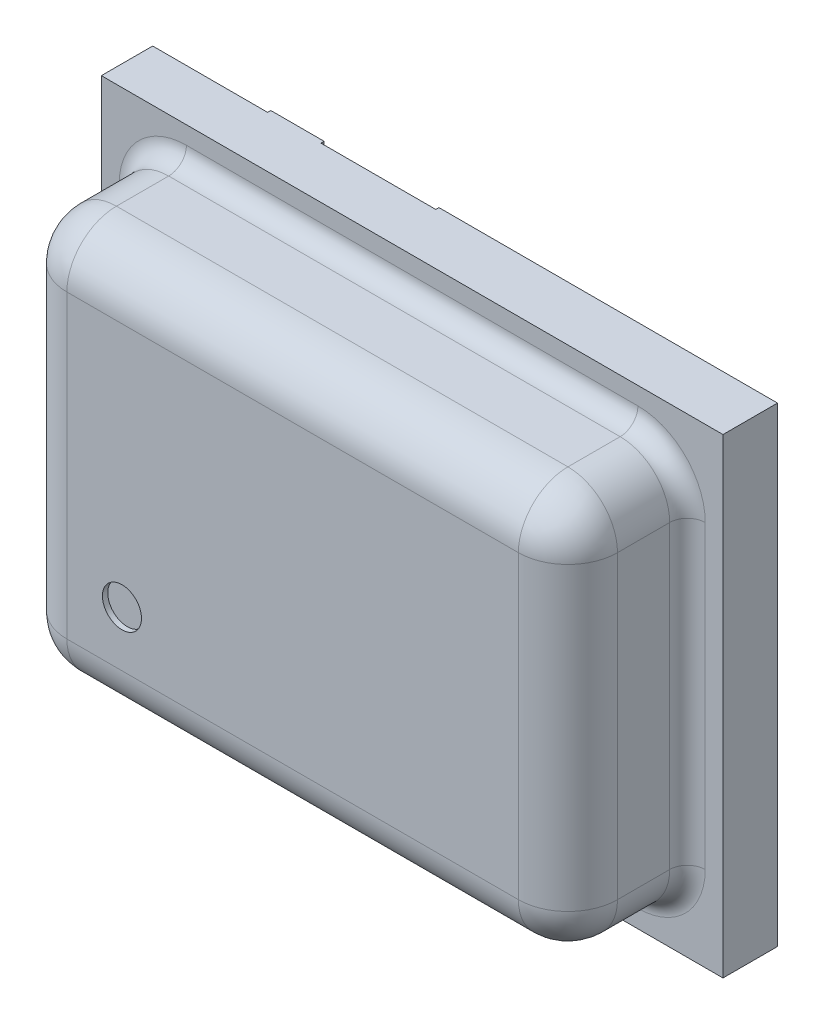
SolidWorks part; units mm, degrees
ref_plane "Front Plane" through (0, 0, 0) normal (0, 0, 1) x (1, 0, 0)
ref_plane "Top Plane" through (0, 0, 0) normal (0, 1, 0) x (1, 0, 0)
ref_plane "Right Plane" through (0, 0, 0) normal (1, 0, 0) x (0, 0, -1)
sketch "Sketch1" plane through (0, 0, 0) normal (0, 0, 1) x (1, 0, 0)
  line L1 (-1.75, 1.325) -> (1.75, 1.325)
  line L2 (-1.75, 1.325) -> (-1.75, -1.325)
  line L3 (-1.75, -1.325) -> (1.75, -1.325)
  line L4 (1.75, 1.325) -> (1.75, -1.325)
  line L5 (-1.75, 1.325) -> (1.75, -1.325) construction
  line L6 (-1.75, -1.325) -> (1.75, 1.325) construction
  point P0 (0, 0)
  dimension "D1" = 3.5
  dimension "D2" = 2.65
extrude "Boss-Extrude1" add sketch "Sketch1" along normal blind 0.307
sketch "Sketch2" plane through (0, 0, 0.307) normal (0, 0, 1) x (1, 0, 0)
  line L1 (-1.55, 1.125) -> (1.55, 1.125)
  line L2 (-1.55, 1.125) -> (-1.55, -1.125)
  line L3 (-1.55, -1.125) -> (1.55, -1.125)
  line L4 (1.55, 1.125) -> (1.55, -1.125)
  line L5 (-1.55, 1.125) -> (1.55, -1.125) construction
  line L6 (-1.55, -1.125) -> (1.55, 1.125) construction
  point P0 (0, 0)
  dimension "D1" = 3.1
  dimension "D2" = 2.25
extrude "Boss-Extrude2" add sketch "Sketch2" along normal offset from surface (0.673 mm away) 0.98 up to face at (0, 0, 0)
fillet "Fillet1" radius 0.279 8 edges at (-1.55, 0, 0.98) (0, 1.125, 0.98) (1.55, 0, 0.98) (0, -1.125, 0.98) (-1.55, 1.125, 0.6435) (1.55, 1.125, 0.6435) (1.55, -1.125, 0.6435) (-1.55, -1.125, 0.6435)
sketch "Sketch3" plane through (0, 0, 0.98) normal (0, 0, 1) x (1, 0, 0)
  line L3 (-1.271, 0.846) -> (-1.271, -0.846) construction
  line L4 (-1.271, -0.846) -> (1.271, -0.846) construction
  circle A0 centre (-0.961, -0.536) radius 0.11
  point P2 (-1.071, -0.536)
  point P3 (-0.961, -0.646)
  dimension "D3" = 0.22
  dimension "D1" = 0.2
  dimension "D2" = 0.2
extrude "Cut-Extrude1" cut sketch "Sketch3" against normal blind 0.03
fillet "Fillet2" radius 0.1 8 edges at (1.4683, -1.0433, 0.307) (0, -1.125, 0.307) (-1.4683, -1.0433, 0.307) (-1.55, 0, 0.307) (-1.4683, 1.0433, 0.307) (0, 1.125, 0.307) (1.4683, 1.0433, 0.307) (1.55, 0, 0.307)
sketch "Sketch4" plane through (0, 0, 0) normal (0, 0, -1) x (1, 0, 0)
  line L1 (1.75, 1.325) -> (1.75, -1.325) construction
  circle A0 centre (0.71, 0) radius 0.1625
  dimension "D2" = 0.325
  dimension "D1" = 1.04
extrude "Cut-Extrude2" cut sketch "Sketch4" against normal blind 0.5
sketch "Sketch5" plane through (0, 0, 0) normal (0, 0, -1) x (1, 0, 0)
  line L0 (-1.75, 1.325) -> (1.75, 1.325) construction
  line L1 (-1.75, 1.325) -> (-1.103, 1.325)
  line L2 (-1.75, 1.325) -> (-1.75, 0.475)
  line L3 (-1.75, 0.475) -> (-1.103, 0.475)
  line L4 (-1.103, 1.325) -> (-1.103, 0.475)
  line L5 (1.75, -1.325) -> (-1.75, -1.325) construction
  line L6 (-0.803, 1.325) -> (-0.156, 1.325)
  line L7 (-0.803, 1.325) -> (-0.803, 0.475)
  line L8 (-0.803, 0.475) -> (-0.156, 0.475)
  line L9 (-0.156, 1.325) -> (-0.156, 0.475)
  line L10 (-1.75, -1.325) -> (-1.103, -1.325)
  line L11 (-1.75, -1.325) -> (-1.75, -0.475)
  line L12 (-1.75, -0.475) -> (-1.103, -0.475)
  line L13 (-1.103, -1.325) -> (-1.103, -0.475)
  line L14 (-1.75, -1.325) -> (-1.75, 1.325) construction
  line L15 (-0.803, -1.325) -> (-0.156, -1.325)
  line L16 (-0.803, -1.325) -> (-0.803, -0.475)
  line L17 (-0.803, -0.475) -> (-0.156, -0.475)
  line L18 (-0.156, -1.325) -> (-0.156, -0.475)
  circle A0 centre (0.71, 0) radius 0.5125
  circle A1 centre (0.71, 0) radius 0.8125
  circle A2 centre (0.71, 0) radius 0.2875
  circle A3 centre (0.71, 0) radius 0.1625 construction
  circle M15 centre (0.71, 0) radius 0.1625
  line M17 (1.75, 1.325) -> (-1.75, 1.325)
  line M18 (-1.75, 1.325) -> (-1.75, -1.325)
  line M19 (-1.75, -1.325) -> (1.75, -1.325)
  dimension "D4" = 1.625
  dimension "D5" = 1.025
  dimension "D6" = 0.125
  dimension "D1" = 0.3
  dimension "D2" = 0.647
  dimension "D3" = 0.95
extrude "Cut-Extrude3" cut sketch "Sketch5" against normal blind 0.018 contours L9 L7 L8 M17 | L4 L3 M17 M18 | L13 L12 M19 M18 | L18 L17 L16 M19 | A1 A0 | A2 M15
sketch "Sketch6" plane through (0, 0, 0.018) normal (0, 0, -1) x (1, 0, 0)
  line L1 (-1.103, 0.475) -> (-1.625, 0.475)
  line L2 (-1.103, 0.475) -> (-1.103, 1.2)
  line L3 (-1.103, 1.2) -> (-1.625, 1.2)
  line L4 (-1.625, 0.475) -> (-1.625, 1.2)
  line L5 (-0.803, 0.475) -> (-0.281, 0.475)
  line L6 (-0.803, 0.475) -> (-0.803, 1.2)
  line L7 (-0.803, 1.2) -> (-0.281, 1.2)
  line L8 (-0.281, 0.475) -> (-0.281, 1.2)
  line L9 (-0.803, -0.475) -> (-0.281, -0.475)
  line L10 (-0.803, -0.475) -> (-0.803, -1.2)
  line L11 (-0.803, -1.2) -> (-0.281, -1.2)
  line L12 (-0.281, -0.475) -> (-0.281, -1.2)
  line L13 (-1.103, -0.475) -> (-1.625, -0.475)
  line L14 (-1.103, -0.475) -> (-1.103, -1.2)
  line L15 (-1.103, -1.2) -> (-1.625, -1.2)
  line L16 (-1.625, -0.475) -> (-1.625, -1.2)
  line L18 (-1.75, -1.325) -> (-1.103, -1.325) construction
  line L19 (-1.75, -0.475) -> (-1.75, -1.325) construction
  circle A0 centre (0.71, 0) radius 0.8125
  circle A1 centre (0.71, 0) radius 0.5125
  dimension "D1" = 0.125
  dimension "D2" = 0.125
extrude "Boss-Extrude3" add sketch "Sketch6" along normal blind 0.018
